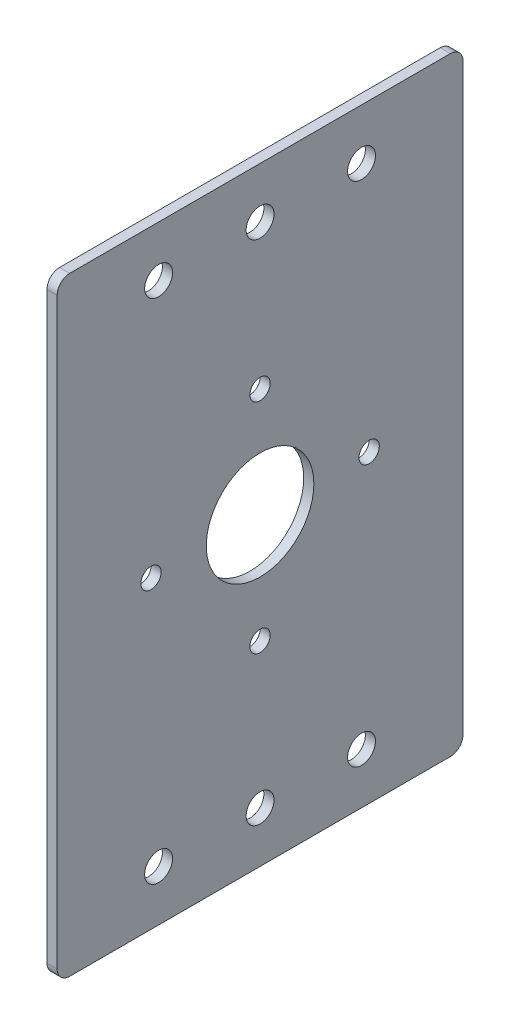
SolidWorks part; units mm, degrees
material "5052-H32"
ref_plane "Front Plane" through (0, 0, 0) normal (0, 0, 1) x (1, 0, 0)
ref_plane "Top Plane" through (0, 0, 0) normal (0, 1, 0) x (1, 0, 0)
ref_plane "Right Plane" through (0, 0, 0) normal (1, 0, 0) x (0, 0, -1)
sketch "Sketch1" plane through (0, 0, 0) normal (1, 0, 0) x (0, 0, -1)
  line L0 (0, 152.4) -> (101.6, 0) construction
  line L1 (0, 0) -> (101.6, 0)
  line L2 (0, 0) -> (0, 152.4)
  line L3 (0, 152.4) -> (101.6, 152.4)
  line L4 (101.6, 0) -> (101.6, 152.4)
  line L5 (101.6, 152.4) -> (0, 0) construction
  line L6 (50.8, 76.2) -> (78.105, 76.2) construction
  line L7 (50.8, 76.2) -> (50.8, 48.895) construction
  line L8 (50.8, 76.2) -> (23.495, 76.2) construction
  line L9 (50.8, 76.2) -> (50.8, 103.505) construction
  line L10 (0, 76.2) -> (101.6, 76.2) construction
  circle A0 centre (78.105, 76.2) radius 2.54
  circle A1 centre (50.8, 76.2) radius 13.462
  circle A2 centre (50.8, 48.895) radius 2.54
  circle A3 centre (23.495, 76.2) radius 2.54
  circle A4 centre (50.8, 103.505) radius 2.54
  point P5 (89.0178, 85.4797)
  point P19 (50.8, 76.2)
  dimension "D1" = 27.305
  dimension "D2" = 152.4
  dimension "D3" = 101.6
  dimension "D4" = 4
extrude "Boss-Extrude2" add sketch "Sketch1" along normal blind 2.54
sketch "Sketch2" plane through (2.54, 0, 0) normal (1, 0, 0) x (0, 0, -1)
  line L1 (101.6, 152.4) -> (0, 152.4) construction
  line L2 (0, 0) -> (101.6, 0) construction
  circle A0 centre (50.8, 139.7) radius 3.4925
  circle A1 centre (50.8, 12.7) radius 3.4925
  point P11 (50.8, 152.4)
  dimension "D1" = 6.985
  dimension "D2" = 12.7
  dimension "D3" = 12.7
extrude "Cut-Extrude1" cut sketch "Sketch2" against normal through all
pattern_linear "LPattern2" count 2 spacing 25.4 along (0, 0, -1) of "Cut-Extrude1"
pattern_linear "LPattern3" count 2 spacing 25.4 along (0, 0, 1) of "Cut-Extrude1"
fillet "Fillet1" radius 3.175 4 edges at (1.27, 0, -101.6) (1.27, 0, 0) (1.27, 152.4, -101.6) (1.27, 152.4, 0)
equation "\"AdditionalMountingHoles\"= 2"
equation "\"HoleSpacing\"= 1in"
equation "\"D2@Sketch1\"=\"ROVHeight@Assem2.SLDASM\""
equation "\"D3@Sketch1\"= ( \"AdditionalMountingHoles\" + 2 ) * \"HoleSpacing\""
equation "\"MountingHoleSize\"= .275in"
equation "\"D1@Sketch2\"=\"MountingHoleSize\""
equation "\"D3@LPattern2\"=\"HoleSpacing\""
equation "\"D3@LPattern3\"=\"HoleSpacing\""
equation "\"D1@LPattern3\"=\"AdditionalMountingHoles\""
equation "\"D1@LPattern2\"=\"AdditionalMountingHoles\""
